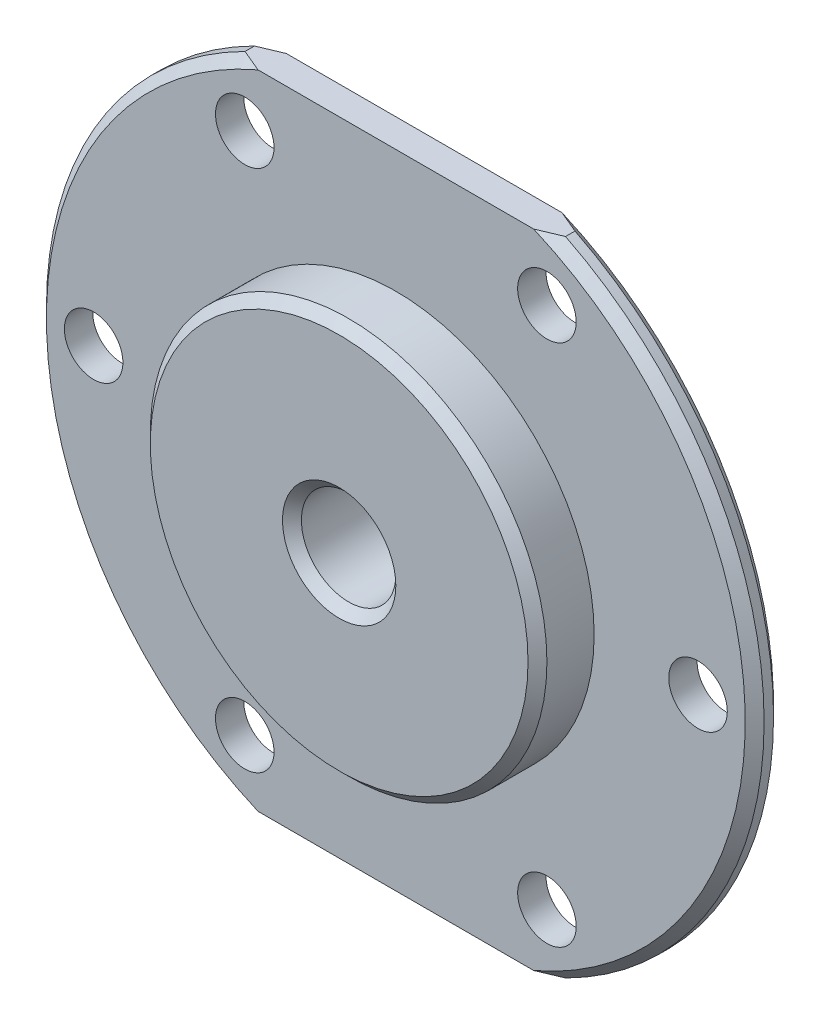
SolidWorks part; units mm, degrees
ref_plane "Front Plane" through (0, 0, 0) normal (0, 0, 1) x (1, 0, 0)
ref_plane "Top Plane" through (0, 0, 0) normal (0, 1, 0) x (1, 0, 0)
ref_plane "Right Plane" through (0, 0, 0) normal (1, 0, 0) x (0, 0, -1)
sketch "Sketch2" plane through (0, 0, 0) normal (0, 0, 1) x (1, 0, 0)
  line L0 (-8.4853, 17) -> (8.4853, 17)
  line L1 (-8.4853, -17) -> (8.4853, -17)
  arc A0 (-8.4853, 17) -> (-8.4853, -17) centre (0, 0) ccw
  circle A1 centre (0, 0) radius 16 construction
  arc A2 (8.4853, -17) -> (8.4853, 17) centre (0, 0) ccw
  circle A3 centre (-16, 0) radius 1.55
  circle A4 centre (-8, 13.8564) radius 1.55
  circle A5 centre (8, 13.8564) radius 1.55
  circle A6 centre (16, 0) radius 1.55
  circle A7 centre (8, -13.8564) radius 1.55
  circle A8 centre (-8, -13.8564) radius 1.55
  point P22 (0, 0)
  dimension "D1" = 38
  dimension "D2" = 17
  dimension "D3" = 32
  dimension "D5" = 3.1
  dimension "D4" = 17
  dimension "D6" = 6
extrude "Boss-Extrude1" add sketch "Sketch2" along normal blind 1.5
sketch "Sketch3" plane through (0, 0, 1.5) normal (0, 0, 1) x (1, 0, 0)
  circle A0 centre (0, 0) radius 10.5
  dimension "D1" = 21
extrude "Boss-Extrude2" add sketch "Sketch3" along normal blind 3
sketch "Sketch4" plane through (0, 0, 0) normal (0, 0, -1) x (-1, 0, 0)
  circle A0 centre (0, 0) radius 5
  dimension "D1" = 10
extrude "Boss-Extrude3" add sketch "Sketch4" along normal blind 5
sketch "Sketch5" plane through (0, 0, 4.5) normal (0, 0, 1) x (1, 0, 0)
  circle A0 centre (0, 0) radius 2.5
  dimension "D1" = 5
extrude "Cut-Extrude1" cut sketch "Sketch5" against normal through all
chamfer "Chamfer1" distance 0.5 angle 45 8 edges at (-5, 0, -5) (2.5, 0, -5) (-19, 0, 1.5) (-19, 0, 0) (19, 0, 0) (19, 0, 1.5) (2.5, 0, 4.5) (10.5, 0, 4.5)
